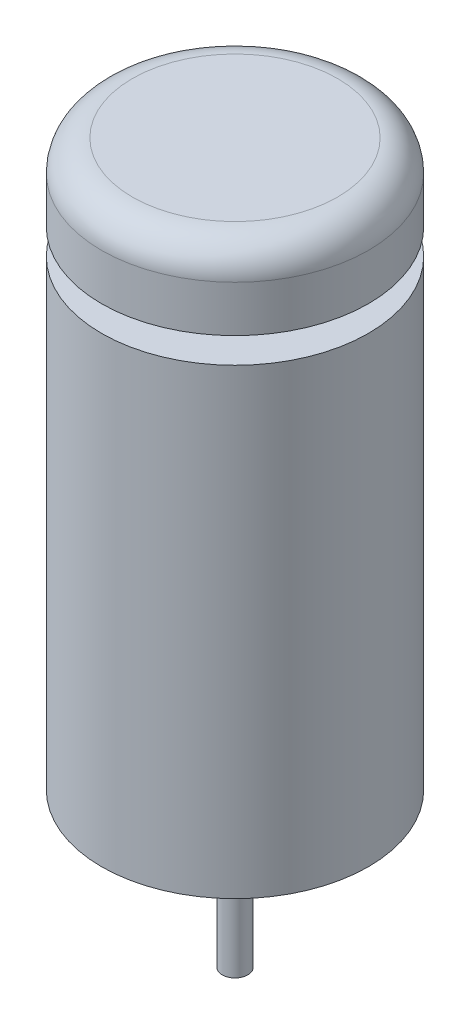
SolidWorks part; units mm, degrees
ref_plane "Front Plane" through (0, 0, 0) normal (0, 0, 1) x (1, 0, 0)
ref_plane "Top Plane" through (0, 0, 0) normal (0, 1, 0) x (1, 0, 0)
ref_plane "Right Plane" through (0, 0, 0) normal (1, 0, 0) x (0, 0, -1)
sketch "Sketch1" plane through (0, 0, 0) normal (0, 1, 0) x (1, 0, 0)
  circle A0 centre (0, 0) radius 26
  dimension "D1" = 52
extrude "Boss-Extrude1" add sketch "Sketch1" along normal blind 90
sketch "Sketch2" plane through (0, 90, 0) normal (0, 1, 0) x (1, 0, 0)
  circle A0 centre (0, 0) radius 8.6386
extrude "Boss-Extrude2" add sketch "Sketch2" along normal blind 5
sketch "Sketch3" plane through (0, 95, 0) normal (0, 1, 0) x (1, 0, 0)
  circle A0 centre (0, 0) radius 26
  circle A1 centre (0, 0) radius 26 construction
extrude "Boss-Extrude3" add sketch "Sketch3" along normal blind 15
sketch "Sketch4" plane through (0, 0, 0) normal (0, -1, 0) x (1, 0, 0)
  circle A0 centre (0, 0) radius 10.6747
extrude "Boss-Extrude4" add sketch "Sketch4" along normal blind 5
sketch "Sketch5" plane through (0, -5, 0) normal (0, -1, 0) x (1, 0, 0)
  circle A0 centre (0, 0) radius 2.5
  dimension "D1" = 5
extrude "Boss-Extrude5" add sketch "Sketch5" along normal blind 25 contours A0
fillet "Fillet1" radius 6 1 edges at (0, 110, 26)
